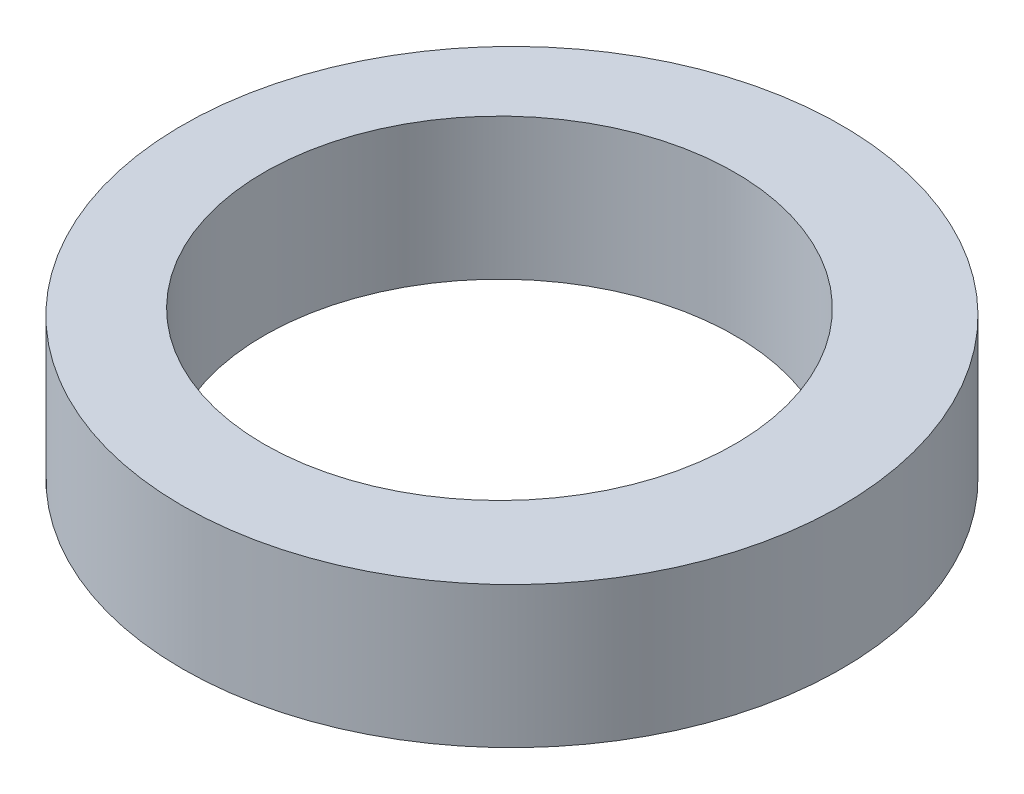
SolidWorks part; units mm, degrees
ref_plane "前视基准面" through (0, 0, 0) normal (0, 0, 1) x (1, 0, 0)
ref_plane "上视基准面" through (0, 0, 0) normal (0, 1, 0) x (1, 0, 0)
ref_plane "右视基准面" through (0, 0, 0) normal (1, 0, 0) x (0, 0, -1)
sketch "草图1" plane through (0, 0, 0) normal (0, 1, 0) x (1, 0, 0)
  circle A0 centre (0, 0) radius 12.5
  circle A1 centre (0.6616, 0) radius 17.5
  dimension "D1" = 25
  dimension "D2" = 35
extrude "凸台-拉伸1" add sketch "草图1" along normal blind 7.5
